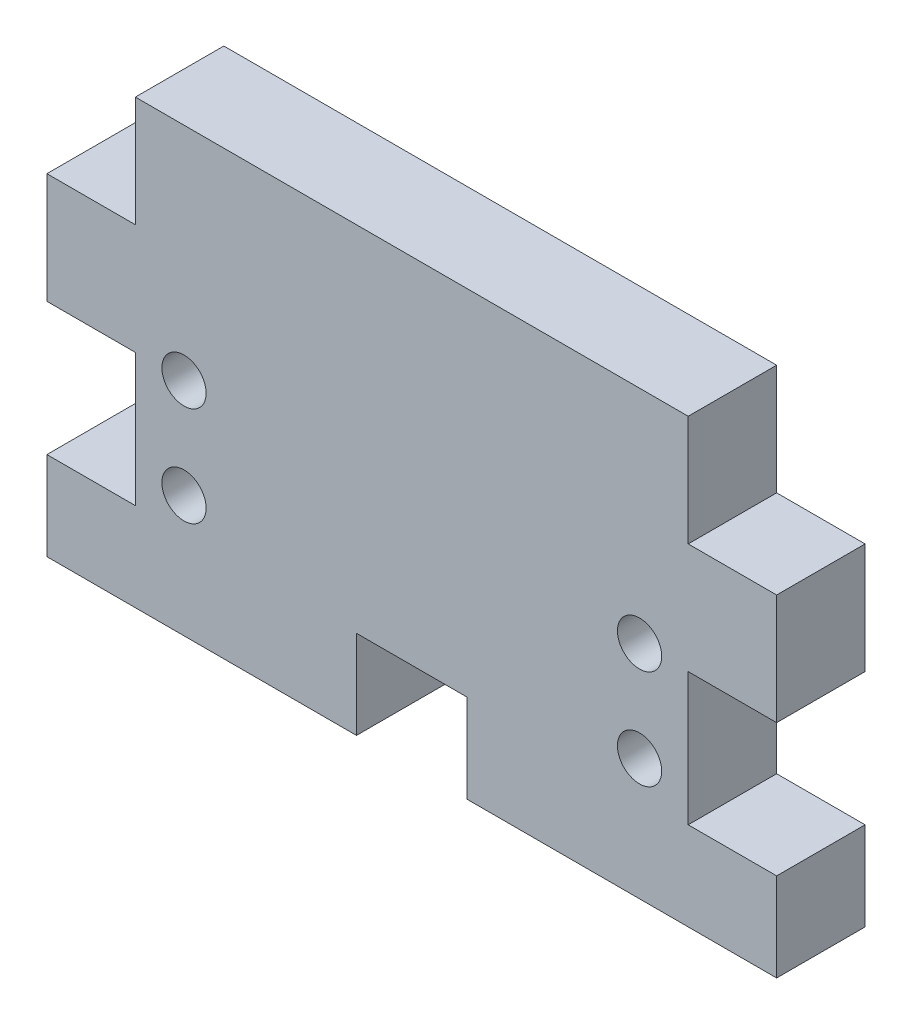
SolidWorks part; units mm, degrees
ref_plane "Спереди" through (0, 0, 0) normal (0, 0, 1) x (1, 0, 0)
ref_plane "Сверху" through (0, 0, 0) normal (0, 1, 0) x (1, 0, 0)
ref_plane "Справа" through (0, 0, 0) normal (1, 0, 0) x (0, 0, -1)
other "Configuration Table"
sketch "Эскиз1" plane through (0, 0, 0) normal (0, 0, 1) x (1, 0, 0)
  line L1 (0, 0) -> (33, 0)
  line L2 (0, 0) -> (0, 20)
  line L3 (0, 20) -> (33, 20)
  line L4 (33, 0) -> (33, 20)
  dimension "D1" = 20
  dimension "D2" = 33
extrude "Бобышка-Вытянуть1" add sketch "Эскиз1" along normal blind 4
sketch "Эскиз2" plane through (0, 0, 0) normal (0, 0, -1) x (-1, 0, 0)
  line L0 (0, 20) -> (0, 0) construction
  line L1 (-4, 15) -> (0, 15)
  line L2 (-4, 15) -> (-4, 20)
  line L3 (-4, 20) -> (0, 20)
  line L4 (0, 15) -> (0, 20)
  line L5 (-33, 20) -> (0, 20) construction
  line L6 (0, 0) -> (-33, 0) construction
  line L7 (0, 10) -> (-4, 10)
  line L8 (0, 10) -> (0, 4)
  line L9 (0, 4) -> (-4, 4)
  line L10 (-4, 10) -> (-4, 4)
  line L11 (-14, 4) -> (-19, 4)
  line L12 (-14, 4) -> (-14, 0)
  line L13 (-14, 0) -> (-19, 0)
  line L14 (-19, 4) -> (-19, 0)
  line L15 (-16.5, 0) -> (-16.5, 20) construction
  line L16 (-29, 10) -> (-29, 4)
  line L17 (-33, 4) -> (-29, 4)
  line L18 (-33, 10) -> (-33, 4)
  line L19 (-33, 10) -> (-29, 10)
  line L20 (-33, 15) -> (-33, 20)
  line L21 (-29, 20) -> (-33, 20)
  line L22 (-29, 15) -> (-29, 20)
  line L23 (-29, 15) -> (-33, 15)
extrude "Вырез-Вытянуть1" cut sketch "Эскиз2" against normal blind 4
sketch "Эскиз3" plane through (0, 0, 4) normal (0, 0, 1) x (1, 0, 0)
  line L0 (16.5, 20) -> (16.5, 4) construction
  line L1 (29, 20) -> (4, 20) construction
  line L2 (14, 4) -> (19, 4) construction
  circle A0 centre (6.2, 10) radius 1
  circle A1 centre (26.8, 10) radius 1
  circle A2 centre (6.2, 5.5) radius 1
  circle A3 centre (26.8, 5.5) radius 1
  dimension "D1" = 2
  dimension "D2" = 20.6
  dimension "D4" = 1.5
  dimension "D5" = 6
  dimension "D3" = 2
extrude "Вырез-Вытянуть2" cut sketch "Эскиз3" against normal blind 4
